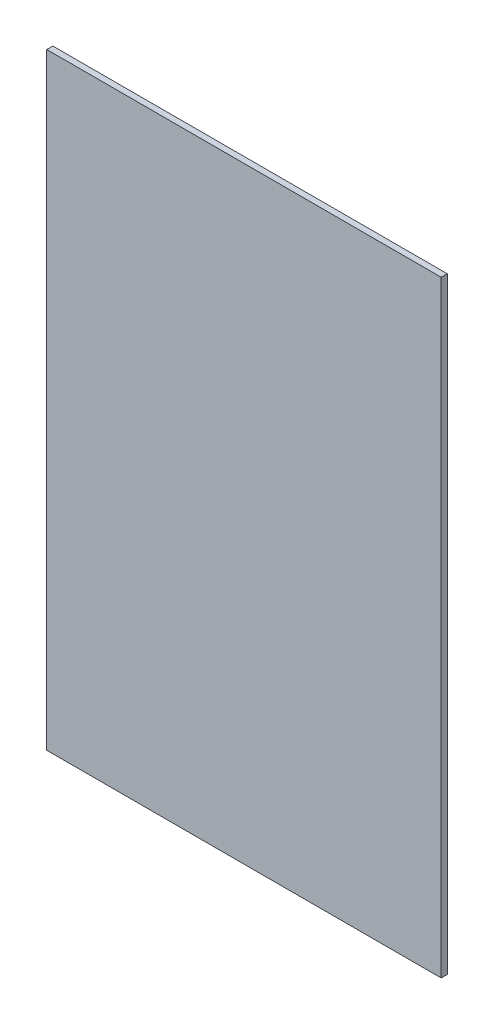
SolidWorks part; units mm, degrees
ref_plane "Plan de face" through (0, 0, 0) normal (0, 0, 1) x (1, 0, 0)
ref_plane "Plan de dessus" through (0, 0, 0) normal (0, 1, 0) x (1, 0, 0)
ref_plane "Plan de droite" through (0, 0, 0) normal (1, 0, 0) x (0, 0, -1)
sketch "Esquisse1" plane through (0, 0, 0) normal (0, 0, 1) x (1, 0, 0)
  line L1 (0, 0) -> (650, 0)
  line L2 (0, 0) -> (0, -1000)
  line L3 (0, -1000) -> (650, -1000)
  line L4 (650, 0) -> (650, -1000)
  dimension "D1" = 650
  dimension "D2" = 1000
extrude "Boss.-Extru.2" add sketch "Esquisse1" along normal blind 10 contours L2 L3 L4 L1
